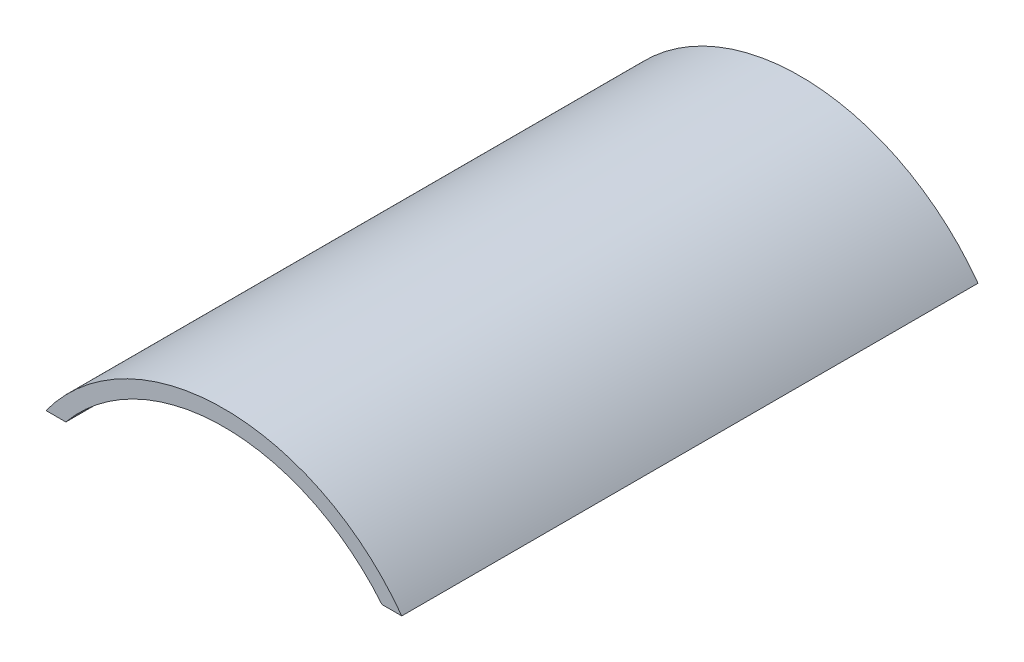
SolidWorks part; units mm, degrees
ref_plane "Front Plane" through (0, 0, 0) normal (0, 0, 1) x (1, 0, 0)
ref_plane "Top Plane" through (0, 0, 0) normal (0, 1, 0) x (1, 0, 0)
ref_plane "Right Plane" through (0, 0, 0) normal (1, 0, 0) x (0, 0, -1)
sketch "Sketch1" plane through (0, 0, 0) normal (0, 0, 1) x (1, 0, 0)
  line L2 (-15.0839, 12.3583) -> (-16.9786, 12.3583)
  line L3 (15.0839, 12.3583) -> (16.9786, 12.3583)
  line L5 (-17.9749, 10.8583) -> (17.9749, 10.8583) construction
  line L6 (-15.0839, 12.3583) -> (15.0839, 12.3583) construction
  arc A0 (15.0839, 12.3583) -> (-15.0839, 12.3583) centre (0, 0) ccw
  arc A1 (16.9786, 12.3583) -> (-16.9786, 12.3583) centre (0, 0) ccw
  arc A2 (17.9749, 10.8583) -> (-17.9749, 10.8583) centre (0, 0) ccw construction
  dimension "D1" = 39
  dimension "D2" = 1.5
extrude "Boss-Extrude1" add sketch "Sketch1" along normal blind 55 contours A1 L2 A0 L3
